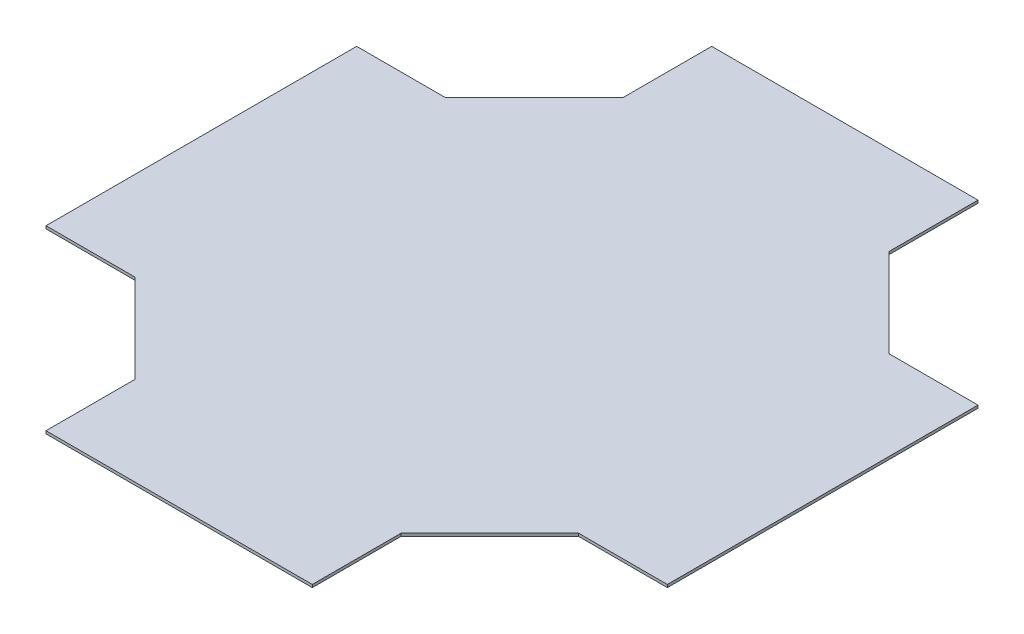
SolidWorks part; units mm, degrees
ref_plane "Front Plane" through (0, 0, 0) normal (0, 0, 1) x (1, 0, 0)
ref_plane "Top Plane" through (0, 0, 0) normal (0, 1, 0) x (1, 0, 0)
ref_plane "Right Plane" through (0, 0, 0) normal (1, 0, 0) x (0, 0, -1)
sketch "Sketch1" plane through (0, 0, 0) normal (0, 1, 0) x (1, 0, 0)
  line L0 (254, 177.8) -> (152.4, 279.4)
  line L1 (-355.6, 177.8) -> (355.6, 177.8)
  line L2 (-355.6, 177.8) -> (-355.6, -177.8)
  line L3 (-355.6, -177.8) -> (355.6, -177.8)
  line L4 (355.6, 177.8) -> (355.6, -177.8)
  line L5 (-355.6, 177.8) -> (355.6, -177.8) construction
  line L6 (-355.6, -177.8) -> (355.6, 177.8) construction
  line L7 (152.4, -381) -> (-152.4, -381)
  line L8 (152.4, -381) -> (152.4, 381)
  line L9 (152.4, 381) -> (-152.4, 381)
  line L10 (-152.4, -381) -> (-152.4, 381)
  line L11 (152.4, -381) -> (-152.4, 381) construction
  line L12 (152.4, 381) -> (-152.4, -381) construction
  line L13 (254, -177.8) -> (152.4, -279.4)
  line L14 (-152.4, 279.4) -> (-254, 177.8)
  line L15 (-254, -177.8) -> (-152.4, -279.4)
  point P0 (0, 0)
  point P6 (0, 0)
  dimension "D1" = 355.6
  dimension "D2" = 711.2
  dimension "D3" = 304.8
  dimension "D4" = 762
  dimension "D5" = 101.6
  dimension "D6" = 101.6
  dimension "D7" = 101.6
  dimension "D8" = 101.6
extrude "Boss-Extrude1" add sketch "Sketch1" along normal mid plane 3.175 contours L3 L10 L1 L2 | L10 L3 L8 L1 | L10 L1 L8 L9 | L10 L7 L8 L3 | L8 L3 L4 L1 | L8 L1 L0 | L13 L3 L8 | L3 L15 L10 | L10 L14 L1
